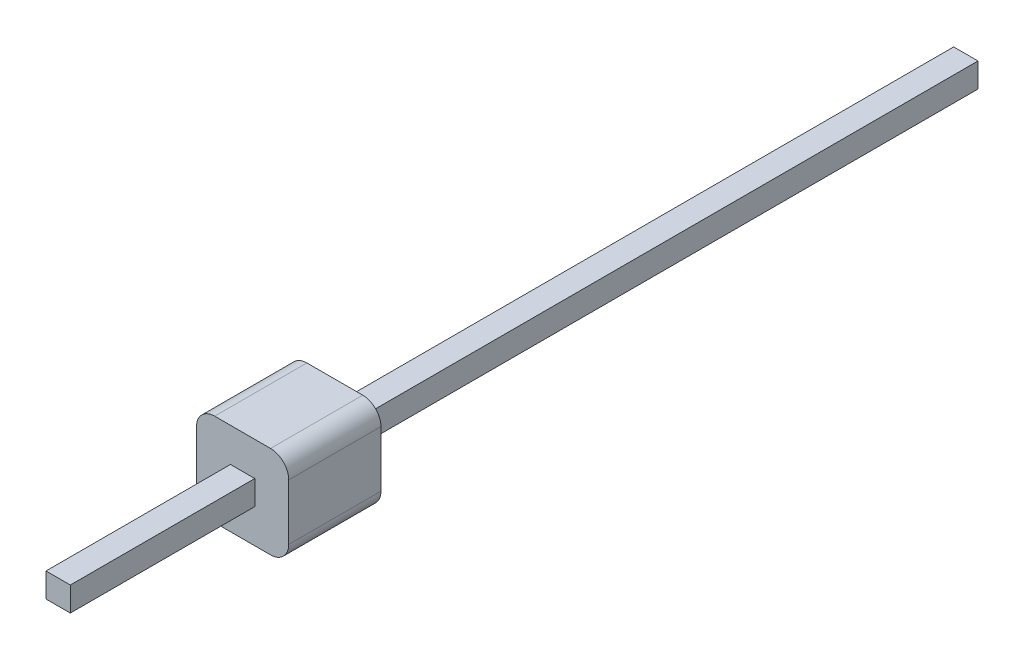
SolidWorks part; units mm, degrees
ref_plane "前视基准面" through (0, 0, 0) normal (0, 0, 1) x (1, 0, 0)
ref_plane "上视基准面" through (0, 0, 0) normal (0, 1, 0) x (1, 0, 0)
ref_plane "右视基准面" through (0, 0, 0) normal (1, 0, 0) x (0, 0, -1)
sketch "草图1" plane through (0, 0, 0) normal (0, 0, 1) x (1, 0, 0)
  line L0 (0, 5.3599) -> (0, -8.0108) construction
  line L1 (-1.27, -0.0191) -> (1.27, -0.0191)
  line L2 (-1.27, -0.0191) -> (-1.27, -2.5591)
  line L3 (-1.27, -2.5591) -> (1.27, -2.5591)
  line L4 (1.27, -0.0191) -> (1.27, -2.5591)
  dimension "D1" = 2.54
  dimension "D2" = 2.54
extrude "拉伸1" add sketch "草图1" along normal blind 2.54
ref_plane "基准面1" through (0, 0, 7.62) normal (0, 0, -1) x (-1, 0, 0)
sketch "草图2" plane through (0, 0, 7.62) normal (0, 0, -1) x (-1, 0, 0)
  line L0 (-1.27, -1.2891) -> (1.27, -1.2891) construction
  line L1 (-1.27, -2.5591) -> (-1.27, -0.0191) construction
  line L2 (1.27, -0.0191) -> (1.27, -2.5591) construction
  line L3 (0, 1.9407) -> (0, -4.2425) construction
  line L5 (-0.335, -0.9541) -> (0.335, -0.9541)
  line L6 (-0.335, -0.9541) -> (-0.335, -1.6241)
  line L7 (-0.335, -1.6241) -> (0.335, -1.6241)
  line L8 (0.335, -0.9541) -> (0.335, -1.6241)
  dimension "D1" = 0.67
  dimension "D2" = 0.67
sketch "草图3" plane through (0, 0, 0) normal (1, 0, 0) x (0, 0, -1)
  line L0 (17.38, -1.2991) -> (-7.62, -1.2991)
  line L1 (-7.62, 1.9407) -> (-7.62, -4.2425) construction
  line L8 (-2.54, -0.0191) -> (0, -0.0191) construction
  line L9 (0, -2.5591) -> (0, -0.0191) construction
  point P11 (2.54, -1.2991)
  dimension "D1" = 7.62
  dimension "D2" = 25
  dimension "D4" = 1.28
sweep "扫描1" add profiles "草图2" path "草图3"
fillet "圆角1" radius 0.5 4 edges at (1.27, -0.0191, 1.27) (1.27, -2.5591, 1.27) (-1.27, -2.5591, 1.27) (-1.27, -0.0191, 1.27)
